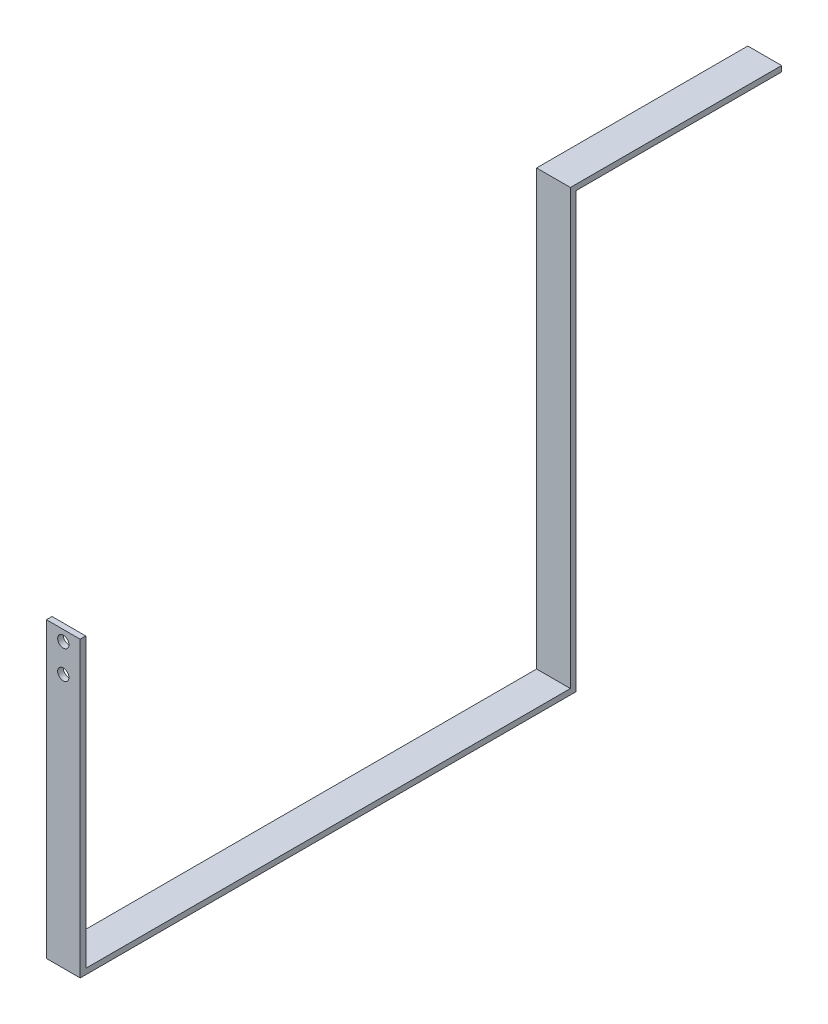
SolidWorks part; units mm, degrees
ref_plane "Alzado" through (0, 0, 0) normal (0, 0, 1) x (1, 0, 0)
ref_plane "Planta" through (0, 0, 0) normal (0, 1, 0) x (1, 0, 0)
ref_plane "Vista lateral" through (0, 0, 0) normal (1, 0, 0) x (0, 0, -1)
sketch "Croquis1" plane through (0, 0, 0) normal (0, 0, 1) x (1, 0, 0)
  line L1 (-19.05, -3.155) -> (19.05, -3.155)
  line L2 (-19.05, -3.155) -> (-19.05, 3.155)
  line L3 (-19.05, 3.155) -> (19.05, 3.155)
  line L4 (19.05, -3.155) -> (19.05, 3.155)
  line L5 (-19.05, -3.155) -> (19.05, 3.155) construction
  line L6 (-19.05, 3.155) -> (19.05, -3.155) construction
  point P0 (0, 0)
  dimension "D1" = 6.31
  dimension "D2" = 38.1
extrude "Saliente-Extruir1" add sketch "Croquis1" along normal blind 238.06
sketch "Croquis2" plane through (0, -3.155, 0) normal (0, -1, 0) x (1, 0, 0)
  line L0 (19.05, 238.06) -> (-19.05, 238.06)
  line L1 (-19.05, 238.06) -> (-19.05, 231.75)
  line L2 (-19.05, 238.06) -> (-19.05, 0) construction
  line L3 (-19.05, 231.75) -> (19.05, 231.75)
  line L4 (19.05, 238.06) -> (19.05, 0) construction
  line L5 (19.05, 231.75) -> (19.05, 238.06)
  dimension "D1" = 6.31
extrude "Saliente-Extruir2" add sketch "Croquis2" along normal blind 489.1
sketch "Croquis3" plane through (0, 0, 238.06) normal (0, 0, 1) x (1, 0, 0)
  line L0 (-19.05, -492.255) -> (19.05, -492.255)
  line L1 (19.05, -492.255) -> (19.05, -485.945)
  line L2 (19.05, -492.255) -> (19.05, 3.155) construction
  line L3 (19.05, -485.945) -> (-19.05, -485.945)
  line L4 (-19.05, 3.155) -> (-19.05, -492.255) construction
  line L5 (-19.05, -485.945) -> (-19.05, -492.255)
  dimension "D1" = 6.31
extrude "Saliente-Extruir3" add sketch "Croquis3" along normal blind 552.5
sketch "Croquis4" plane through (0, -485.945, 0) normal (0, 1, 0) x (1, 0, 0)
  line L0 (19.05, -790.56) -> (-19.05, -790.56)
  line L1 (-19.05, -790.56) -> (-19.05, -784.25)
  line L2 (-19.05, -784.25) -> (19.05, -784.25)
  line L3 (19.05, -790.56) -> (19.05, -238.06) construction
  line L4 (19.05, -784.25) -> (19.05, -790.56)
  dimension "D1" = 6.31
extrude "Saliente-Extruir4" add sketch "Croquis4" along normal blind 324.39
sketch "Croquis5" plane through (0, 0, 790.56) normal (0, 0, 1) x (1, 0, 0)
  circle A0 centre (0, -173.4472) radius 6.35
  circle A1 centre (0, -205.4472) radius 6.35
extrude "Cortar-Extruir1" cut sketch "Croquis5" against normal blind 6.31
